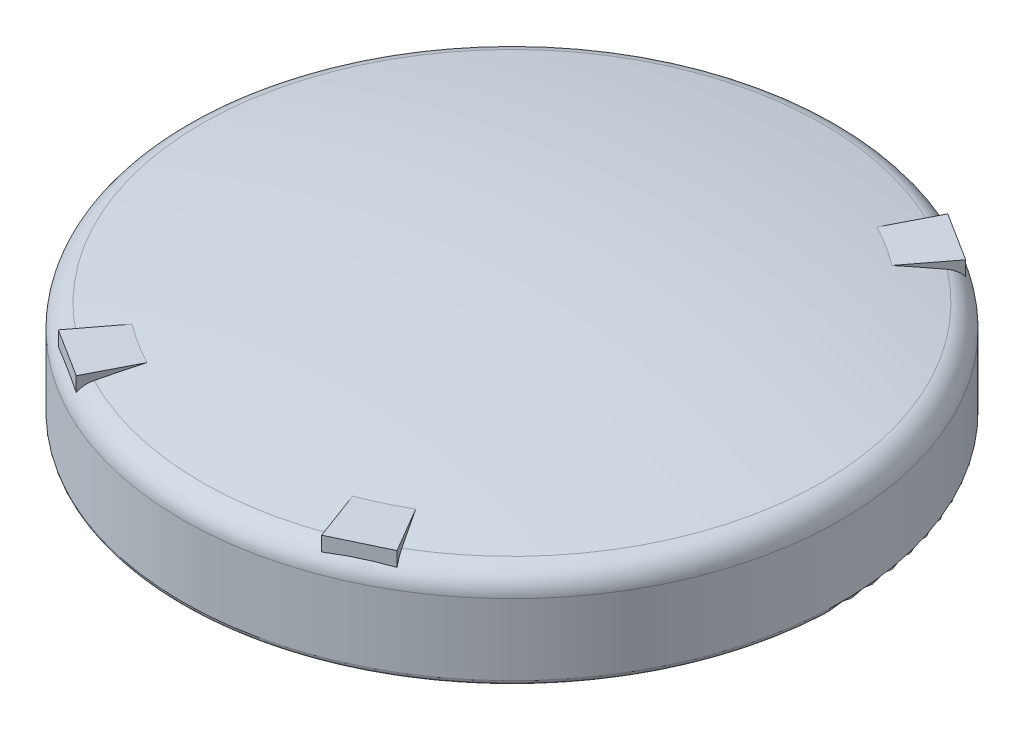
SolidWorks part; units mm, degrees
ref_plane "Front Plane" through (0, 0, 0) normal (0, 0, 1) x (1, 0, 0)
ref_plane "Top Plane" through (0, 0, 0) normal (0, 1, 0) x (1, 0, 0)
ref_plane "Right Plane" through (0, 0, 0) normal (1, 0, 0) x (0, 0, -1)
sketch "Sketch1" plane through (0, 0, 0) normal (0, 0, 1) x (1, 0, 0)
  line L0 (0, 5.2) -> (14, 5.2) construction
  line L1 (11.85, 0.8) -> (11.85, 0.5)
  line L2 (13.8, 0) -> (12.25, 0)
  line L3 (11.85, 0.5) -> (12.25, 0)
  line L4 (12.1792, 4.3) -> (0, 4.3) construction
  line L5 (0, 4.3) -> (0, 5.2) construction
  line L6 (0, 0) -> (0, 12.2062) construction
  line L7 (12.85, 2.8679) -> (12.85, 0.8)
  line L8 (14, 4.0408) -> (14, 0.2) construction
  line L9 (14, 3.2188) -> (14, 0.2)
  line L10 (11.85, 0.8) -> (12.85, 0.8)
  line L11 (14, 5.2) -> (14, 4.0408) construction
  line L12 (12.85, 0.8) -> (12.85, 3.4) construction
  line L13 (0, 5.45) -> (0, 4.65)
  arc A0 (12.85, 3.4) -> (12.1792, 4.3) centre (12.1792, 3.6) ccw construction
  arc A1 (0, 5.45) -> (13.1877, 4.2011) centre (0, -64.8) cw
  arc A2 (0, 4.65) -> (12.2737, 3.5568) centre (0, -64.8) cw
  arc A3 (14, 0.2) -> (13.8, 0) centre (13.8, 0.2) cw
  arc A4 (12.2737, 3.5568) -> (12.85, 2.8679) centre (12.15, 2.8679) cw
  arc A5 (14, 3.2188) -> (13.1877, 4.2011) centre (13, 3.2188) ccw
  point P10 (14.25, 5.2)
  point P11 (11.85, 0)
  point P24 (12.85, 3.4509)
  dimension "D6" = 0.7
  dimension "D7" = 0.4
  dimension "D8" = 12.85
  dimension "D16" = 0.2
  dimension "D12" = 70
  dimension "D13" = 70.25
  dimension "D17" = 69.45
  dimension "D18" = 0.7
  dimension "D19" = 1
  dimension "D1" = 14.25
  dimension "D2" = 5.2
  dimension "D3" = 2.15
  dimension "D4" = 0.5
  dimension "D5" = 0.9
  dimension "D9" = 0
  dimension "D10" = 14
  dimension "D11" = 3.5
  dimension "D14" = 1
  dimension "D15" = 0
revolve "Revolve1" add sketch "Sketch1" angle 360 about L5
ref_plane "Plane1" through (0, 4.5, 0) normal (0, 1, 0) x (1, 0, 0)
sketch "Sketch2" plane through (0, 4.5, 0) normal (0, 1, 0) x (-1, 0, 0)
  line L0 (0, 3.5741) -> (0, -3.9544) construction
  line L1 (11.45, 3.5741) -> (11.45, -4.5126) construction
  line L2 (-4.0315, 0) -> (16.0691, 0) construction
  line L3 (-6, -9.5) -> (6, 9.5) construction
  line L4 (11.45, 0) -> (3.265, 5.1695) construction
  line L5 (3.265, 5.1695) -> (-4.9201, 10.339) construction
  circle A0 centre (-6, -9.5) radius 0.525
  circle A1 centre (-4.9201, 10.339) radius 0.525
  circle A2 centre (6, 9.5) radius 0.525
  circle A3 centre (11.45, 0) radius 0.525 construction
  dimension "D1" = 1.05
  dimension "D2" = 9.5
  dimension "D3" = 6
  dimension "D4" = 1.05
  dimension "D7" = 1.05
  dimension "D9" = 57.724
  dimension "D8" = 11.45
  dimension "D10" = 1.05
  dimension "D5" = 9.5
  dimension "D6" = 6
extrude "Boss-Extrude4" add sketch "Sketch2" against normal blind 3.6 from surface at 0 starting at plane "Plane1"
sketch "Sketch3" plane through (0, 4.5, 0) normal (0, 1, 0) x (-1, 0, 0)
  line L0 (0, 0) -> (13.6975, -1.2009) construction
  line L1 (0, 0) -> (13.6975, 1.2009) construction
  line L2 (0, 0) -> (-6.2786, -12.2328) construction
  line L3 (0, 0) -> (-8.3479, -10.9259) construction
  line L4 (0, 0) -> (8.3479, 10.9259) construction
  line L5 (0, 0) -> (6.2786, 12.2328) construction
  line L6 (5.1103, 9.9566) -> (6.2786, 12.2328)
  line L7 (6.7946, 8.8929) -> (8.3479, 10.9259)
  line L8 (8.3479, 10.9259) -> (6.2786, 12.2328)
  line L9 (11.3627, 0.9962) -> (13.6975, 1.2009) construction
  line L10 (11.3627, -0.9962) -> (13.6975, -1.2009) construction
  line L11 (13.6975, -1.2009) -> (13.6975, 1.2009) construction
  line L12 (-6.7946, -8.8929) -> (-8.3479, -10.9259)
  line L13 (-5.1103, -9.9566) -> (-6.2786, -12.2328)
  line L14 (-6.2786, -12.2328) -> (-8.3479, -10.9259)
  line L15 (0, 0) -> (-4.8015, 12.8844) construction
  line L16 (0, 0) -> (-6.9702, 11.8524) construction
  line L17 (-6.9702, 11.8524) -> (-4.8015, 12.8844)
  line L18 (-4.8015, 12.8844) -> (-3.9831, 10.6882)
  line L19 (-6.9702, 11.8524) -> (-5.7821, 9.8321)
  circle A0 centre (0, 0) radius 13.75 construction
  arc A1 (-5.1103, -9.9566) -> (-6.7946, -8.8929) centre (-6, -9.5) ccw
  arc A2 (-5.7821, 9.8321) -> (-3.9831, 10.6882) centre (-4.9201, 10.339) ccw
  arc A3 (11.3627, 0.9962) -> (11.3627, -0.9962) centre (11.45, 0) ccw construction
  arc A4 (5.1103, 9.9566) -> (6.7946, 8.8929) centre (6, 9.5) ccw
  circle A5 centre (11.45, 0) radius 0.525 construction
  dimension "D3" = 2
  dimension "D2" = 2
  dimension "D4" = 27.5
  dimension "D5" = 2
extrude "Boss-Extrude5" add sketch "Sketch3" against normal blind 2.6 from surface at 0 starting at plane "Plane1"
sketch "Sketch5" plane through (0, 4.5, 0) normal (0, 1, 0) x (-1, 0, 0)
  line L0 (-15.3028, 0) -> (11.45, 0) construction
  line L1 (-4.9201, 10.339) -> (1.375, -2.8895) construction
  circle A0 centre (0, 0) radius 3.2 construction
  circle A1 centre (-3.2, 0) radius 1 construction
  circle A2 centre (1.375, -2.8895) radius 1
  dimension "D1" = 6.4
  dimension "D2" = 2
  dimension "D3" = 2
extrude "Boss-Extrude6" add sketch "Sketch5" against normal blind 1.55 from surface at 0 starting at plane "Plane1"
sketch "Sketch7" plane through (0, 0.8, 0) normal (0, 1, 0) x (1, 0, 0)
  line L0 (0, 0) -> (-11.45, 0) construction
  line L1 (0, 0) -> (10.232, -7.7736) construction
  line L2 (12.0363, -4.5) -> (8.4301, -3.1518)
  line L3 (0, 0) -> (12.0363, -4.5) construction
  line L4 (0, 0) -> (12.0363, 4.5) construction
  line L6 (0, 0) -> (10.4933, 7.4171) construction
  line L7 (0, 0) -> (8.2583, 9.8449) construction
  line L8 (0, 0) -> (3.9139, 12.2394) construction
  line L9 (0, 0) -> (0.6677, 12.8326) construction
  line L10 (0, 0) -> (-12.7337, 1.7252) construction
  line L11 (0, 0) -> (-11.8744, 4.9113) construction
  line L12 (0, 0) -> (-2.6226, 12.5795) construction
  line L13 (0, 0) -> (-10.232, 7.7736) construction
  line L14 (0, 0) -> (-12.7531, -1.5748) construction
  line L15 (0, 0) -> (-11.9315, -4.7709) construction
  line L16 (0, 0) -> (-9.4416, -8.7166) construction
  line L17 (0, 0) -> (-6.9102, -10.8338) construction
  line L18 (0, 0) -> (-3.9232, -12.2365) construction
  line L19 (0, 0) -> (-0.6774, -12.8321) construction
  line L20 (-0.4744, -8.9875) -> (-0.6774, -12.8321)
  line L21 (-3.9232, -12.2365) -> (-2.7478, -8.5703)
  line L22 (-2.7478, -8.5703) -> (-0.4744, -8.9875)
  line L23 (0, 0) -> (2.6226, -12.5795) construction
  line L24 (2.6226, -12.5795) -> (1.8368, -8.8106)
  line L25 (10.232, -7.7736) -> (7.1664, -5.4445)
  line L26 (1.8368, -8.8106) -> (7.1664, -5.4445)
  line L27 (-6.9102, -10.8338) -> (-4.8399, -7.5879)
  line L28 (-9.4416, -8.7166) -> (-6.6128, -6.105)
  line L29 (-6.6128, -6.105) -> (-4.8399, -7.5879)
  line L30 (-11.9315, -4.7709) -> (-8.3567, -3.3415)
  line L31 (-12.7531, -1.5748) -> (-8.9322, -1.103)
  line L32 (-8.9322, -1.103) -> (-8.3567, -3.3415)
  line L33 (-12.7337, 1.7252) -> (-8.9185, 1.2083)
  line L34 (-11.8744, 4.9113) -> (-8.3167, 3.4398)
  line L35 (-8.3167, 3.4398) -> (-8.9185, 1.2083)
  line L36 (-10.232, 7.7736) -> (-7.1664, 5.4445)
  line L37 (-2.6226, 12.5795) -> (-1.8368, 8.8106)
  line L38 (-1.8368, 8.8106) -> (-7.1664, 5.4445)
  line L39 (0, 0) -> (6, -9.5) construction
  line L40 (12.0363, 4.5) -> (8.4301, 3.1518)
  line L41 (-6, 9.5) -> (0, 0) construction
  line L42 (8.4301, 3.1518) -> (8.4301, -3.1518)
  line L43 (0.6677, 12.8326) -> (0.4676, 8.9878)
  line L44 (3.9139, 12.2394) -> (2.7413, 8.5724)
  line L45 (0.4676, 8.9878) -> (2.7413, 8.5724)
  line L46 (8.2583, 9.8449) -> (5.784, 6.8953)
  line L47 (10.4933, 7.4171) -> (7.3494, 5.1948)
  line L48 (7.3494, 5.1948) -> (5.784, 6.8953)
  circle A0 centre (0, 0) radius 12.85 construction
  circle A1 centre (0, 0) radius 9 construction
  arc A2 (10.4933, 7.4171) -> (8.2583, 9.8449) centre (0, 0) ccw
  arc A3 (2.6226, -12.5795) -> (10.232, -7.7736) centre (0, 0) ccw
  arc A4 (-0.6774, -12.8321) -> (-3.9232, -12.2365) centre (0, 0) cw
  arc A5 (-6.9102, -10.8338) -> (-9.4416, -8.7166) centre (0, 0) cw
  arc A6 (-11.9315, -4.7709) -> (-12.7531, -1.5748) centre (0, 0) cw
  arc A7 (-12.7337, 1.7252) -> (-11.8744, 4.9113) centre (0, 0) cw
  arc A8 (-10.232, 7.7736) -> (-2.6226, 12.5795) centre (0, 0) cw
  arc A9 (12.0363, 4.5) -> (12.0363, -4.5) centre (0, 0) cw
  arc A10 (3.9139, 12.2394) -> (0.6677, 12.8326) centre (0, 0) ccw
  point P24 (-4.5016, 7.1275)
  point P50 (4.5016, -7.1275)
  point P54 (8.4301, 0)
  dimension "D16" = 9
  dimension "D17" = 3.3
  dimension "D21" = 25.7
  dimension "D22" = 18
  dimension "D3" = 3.3
  dimension "D4" = 3.3
  dimension "D5" = 3.3
  dimension "D6" = 9
  dimension "D8" = 9
  dimension "D9" = 3.3
  dimension "D10" = 3.3
  dimension "D11" = 3.3
  dimension "D12" = 3.3
  dimension "D14" = 3.3
  dimension "D15" = 3.3
  dimension "D18" = 3.3
  dimension "D20" = 3.3
extrude "Cut-Extrude4" [suppressed] cut sketch "Sketch7" against normal blind 10
fillet "Fillet1" [suppressed] radius 10
fillet "Fillet2" [suppressed] radius 0.2
ref_plane "Plane2" through (15, 0, 0) normal (1, 0, 0) x (0, 0, -1)
sketch "Sketch8" plane through (15, 0, 0) normal (1, 0, 0) x (0, 0, -1)
  line L0 (3, 2.45) -> (-3.5, 2.45)
  line L1 (-3.5, 2.45) -> (-3.5, 0.45)
  line L2 (-3.5, 0.45) -> (-1.8, 0.45)
  line L3 (-1.8, 0.45) -> (-1.8, 1.25)
  line L4 (-1.8, 1.25) -> (3, 0.55)
  circle A0 centre (3, 1.5) radius 0.95
  point P11 (0, 0)
  dimension "D1" = 1.9
  dimension "D2" = 3
  dimension "D3" = 1.5
  dimension "D4" = 2
  dimension "D5" = 0.8
  dimension "D7" = 1.7
